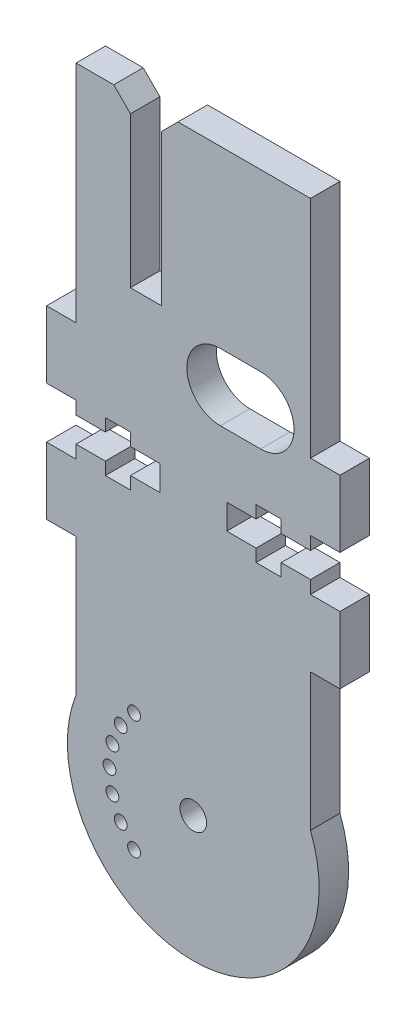
SolidWorks part; units mm, degrees
ref_plane "Front Plane" through (0, 0, 0) normal (0, 0, 1) x (1, 0, 0)
ref_plane "Top Plane" through (0, 0, 0) normal (0, 1, 0) x (1, 0, 0)
ref_plane "Right Plane" through (0, 0, 0) normal (1, 0, 0) x (0, 0, -1)
sketch "Sketch1" plane through (0, 0, 0) normal (0, 0, 1) x (1, 0, 0)
  line L0 (-6.0642, 85.6) -> (22.225, 85.6)
  line L1 (-22.225, 0) -> (22.225, 0)
  line L2 (-22.225, 0) -> (-22.225, 85.6)
  line L3 (-22.225, 85.6) -> (-11.9062, 85.6)
  line L4 (22.225, 0) -> (22.225, 85.6)
  line L6 (-11.9062, 85.6) -> (-11.9062, 53.85)
  line L7 (-11.9062, 53.85) -> (-6.0642, 53.85)
  line L8 (-6.0642, 85.6) -> (-6.0642, 53.85)
  dimension "D1" = 44.45
  dimension "D2" = 85.6
  dimension "D3" = 10.3187
  dimension "D4" = 31.75
  dimension "D5" = 5.842
extrude "Boss-Extrude1" add sketch "Sketch1" along normal mid plane 5.588
sketch "Sketch2" plane through (0, 0, 0) normal (0, 0, 1) x (1, 0, 0)
  line L0 (-22.225, 85.6) -> (-22.225, 0) construction
  line L3 (0, 0) -> (0, 25.4) construction
  line L5 (-6.35, 25.4) -> (6.35, 25.4) construction
  line B0 (-22.225, 27.7812) -> (-16.6688, 27.7812)
  line B1 (-22.225, 23.0187) -> (-16.6688, 23.0187)
  line B2 (-6.35, 27.7812) -> (-6.35, 23.0187)
  line B3 (-22.225, 27.7812) -> (-22.225, 23.0187)
  line B4 (-16.6688, 30.1625) -> (-11.9063, 30.1625)
  line B5 (-16.6688, 30.1625) -> (-16.6688, 27.7812)
  line B6 (-16.6688, 20.6375) -> (-11.9063, 20.6375)
  line B7 (-11.9063, 30.1625) -> (-11.9063, 27.7812)
  line B8 (-16.6688, 23.0187) -> (-16.6688, 20.6375)
  line B9 (-11.9063, 23.0187) -> (-11.9063, 20.6375)
  line B10 (-11.9063, 27.7812) -> (-6.35, 27.7812)
  line B11 (-11.9063, 23.0187) -> (-6.35, 23.0187)
  line B12 (22.225, 27.7812) -> (16.6688, 27.7812)
  line B13 (22.225, 23.0187) -> (16.6688, 23.0187)
  line B14 (6.35, 27.7812) -> (6.35, 23.0187)
  line B15 (22.225, 27.7812) -> (22.225, 23.0187)
  line B16 (16.6688, 30.1625) -> (11.9063, 30.1625)
  line B17 (16.6688, 30.1625) -> (16.6688, 27.7812)
  line B18 (16.6688, 20.6375) -> (11.9063, 20.6375)
  line B19 (11.9063, 30.1625) -> (11.9063, 27.7812)
  line B20 (16.6688, 23.0187) -> (16.6688, 20.6375)
  line B21 (11.9063, 23.0187) -> (11.9063, 20.6375)
  line B22 (11.9063, 27.7812) -> (6.35, 27.7812)
  line B23 (11.9063, 23.0187) -> (6.35, 23.0187)
  dimension "D1" = 25.4
sketch_block_instance "Block2-3"
sketch_block "Block2" parameters "D1"=4.7625, "D2"=4.7625, "D3"=5.5563, "D4"=5.5563
sketch_block_instance "Block2-5"
extrude "Cut-Extrude1" cut sketch "Sketch2" against normal through all both and the other way through all
sketch "Sketch3" plane through (0, 0, 0) normal (0, 0, 1) x (1, 0, 0)
  line L0 (-22.225, 23.0187) -> (-22.225, 0) construction
  line L1 (-22.225, 20.5583) -> (-27.813, 20.5583)
  line L2 (-22.225, 20.5583) -> (-22.225, 7.8583)
  line L3 (-22.225, 7.8583) -> (-27.813, 7.8583)
  line L4 (-27.813, 20.5583) -> (-27.813, 7.8583)
  line L5 (22.225, 0) -> (22.225, 23.0187) construction
  line L6 (22.225, 20.5583) -> (27.813, 20.5583)
  line L7 (22.225, 20.5583) -> (22.225, 7.8583)
  line L8 (22.225, 7.8583) -> (27.813, 7.8583)
  line L9 (27.813, 20.5583) -> (27.813, 7.8583)
  line L11 (-22.225, 85.6) -> (-22.225, 27.7812) construction
  line L12 (-22.225, 30.2417) -> (-27.813, 30.2417)
  line L13 (-22.225, 30.2417) -> (-22.225, 42.9417)
  line L14 (-22.225, 42.9417) -> (-27.813, 42.9417)
  line L15 (-27.813, 30.2417) -> (-27.813, 42.9417)
  line L16 (22.225, 27.7812) -> (22.225, 85.6) construction
  line L17 (22.225, 30.2417) -> (27.813, 30.2417)
  line L18 (22.225, 30.2417) -> (22.225, 42.9417)
  line L19 (22.225, 42.9417) -> (27.813, 42.9417)
  line L20 (27.813, 30.2417) -> (27.813, 42.9417)
  line L21 (-6.35, 25.4) -> (-25.019, 25.4) construction
  line L22 (-6.35, 23.0187) -> (-6.35, 27.7812) construction
  line L23 (-25.019, 30.2417) -> (-25.019, 20.5583) construction
  dimension "D1" = 12.7
  dimension "D2" = 9.6835
  dimension "D3" = 5.588
extrude "Boss-Extrude2" add sketch "Sketch3" along normal up to surface and the other way up to surface up to face at (-1.1232, 33.1156, 2.794) other way up to face at (-1.1232, 33.1156, -2.794)
sketch "Sketch4" plane through (0, 0, 0) normal (0, 0, 1) x (1, 0, 0)
  line L0 (0, -26.8554) -> (0, 0) construction
  line L3 (-22.225, 0) -> (22.225, 0)
  line L4 (-22.225, 0) -> (-22.225, -18.161)
  line L6 (22.225, 0) -> (22.225, -18.161)
  arc A0 (-22.225, -18.161) -> (22.225, -18.161) centre (0, -26.8554) ccw
  circle A1 centre (0, -26.8554) radius 2.5273
  dimension "D1" = 5.0546
  dimension "D2" = 47.7302
  dimension "D3" = 18.161
extrude "Boss-Extrude3" add sketch "Sketch4" along normal up to surface and the other way up to surface up to face at (-0.7488, 30.5438, 2.794) other way up to face at (-0.7488, 30.5438, -2.794)
sketch "Sketch5" plane through (0, 0, 2.794) normal (0, 0, 1) x (1, 0, 0)
  line L0 (-22.225, -26.8554) -> (-9.525, -26.8554) construction
  line L1 (-22.225, -26.5379) -> (-9.525, -26.5379)
  line L2 (-22.225, -27.1729) -> (-9.525, -27.1729)
  line L3 (-9.525, -26.8554) -> (0, -26.8554) construction
  line L4 (-21.9521, -11.8729) -> (-11.8422, -19.5593) construction
  line L5 (-21.7599, -11.6202) -> (-11.65, -19.3066)
  line L6 (-22.1442, -12.1257) -> (-12.0343, -19.812)
  line L7 (-12.667, -0.1113) -> (-9.271, -12.3488) construction
  line L8 (-12.361, -0.0264) -> (-8.9651, -12.2639)
  line L9 (-12.9729, -0.1962) -> (-9.577, -12.4337)
  line L10 (1.8429, 3.632) -> (-2.8602, -8.165) construction
  line L11 (2.1378, 3.5144) -> (-2.5653, -8.2826)
  line L12 (1.548, 3.7496) -> (-3.1552, -8.0475)
  line L13 (15.659, -2.1699) -> (4.7752, -8.7145) construction
  line L14 (15.8227, -2.442) -> (4.9388, -8.9866)
  line L15 (15.4954, -1.8978) -> (4.6116, -8.4424)
  line L16 (23.146, -15.1505) -> (10.5209, -13.7731) construction
  line L17 (23.1115, -15.4661) -> (10.4864, -14.0887)
  line L18 (23.1804, -14.8348) -> (10.5553, -13.4575)
  line L19 (21.2497, -30.0149) -> (12.0331, -21.2774) construction
  line L20 (21.0313, -30.2454) -> (11.8147, -21.5079)
  line L21 (21.4682, -29.7845) -> (12.2516, -21.047)
  line L22 (-8.9633, -41.3931) -> (-0.7298, -31.7236) construction
  line L23 (-9.205, -41.1873) -> (-0.9715, -31.5177)
  line L24 (-8.7215, -41.599) -> (-0.488, -31.9294)
  line L25 (-20.1937, -31.4721) -> (-7.7871, -28.7578) construction
  line L26 (-20.2615, -31.1619) -> (-7.855, -28.4476)
  line L27 (-20.1258, -31.7823) -> (-7.7192, -29.0679)
  line L28 (-23.1292, -16.7775) -> (-11.6101, -22.1255) construction
  line L29 (-22.9955, -16.4895) -> (-11.4764, -21.8376)
  line L30 (-23.2629, -17.0655) -> (-11.7438, -22.4135)
  line L31 (-16.5724, -3.3032) -> (-10.6394, -14.5321) construction
  line L32 (-16.2917, -3.1548) -> (-10.3587, -14.3838)
  line L33 (-16.8531, -3.4515) -> (-10.9201, -14.6805)
  line L34 (-3.1979, 3.4548) -> (-5.271, -9.0749) construction
  line L35 (-2.8846, 3.403) -> (-4.9577, -9.1267)
  line L36 (-3.5111, 3.5066) -> (-5.5842, -9.023)
  line L37 (11.5391, 0.7398) -> (2.3055, -7.9798) construction
  line L38 (11.7571, 0.509) -> (2.5235, -8.2106)
  line L39 (11.3211, 0.9706) -> (2.0875, -7.7489)
  line L2236 (-4.0864, -42.8478) -> (1.8684, -31.6304) construction
  line L2237 (-4.3668, -42.6989) -> (1.588, -31.4815)
  line L2238 (-3.806, -42.9967) -> (2.1488, -31.7793)
  line L2239 (-17.1918, -35.5817) -> (-5.6624, -30.2561) construction
  line L2240 (-17.325, -35.2935) -> (-5.7955, -29.9678)
  line L2241 (-17.0587, -35.8699) -> (-5.5293, -30.5443)
  line L2242 (-23.2268, -21.8658) -> (-10.8256, -24.6042) construction
  line L2243 (-23.1583, -21.5557) -> (-10.7571, -24.2942)
  line L2244 (-23.2953, -22.1758) -> (-10.894, -24.9142)
  line L2245 (-19.7297, -7.2946) -> (-11.515, -16.9801) construction
  line L2246 (-19.4876, -7.0892) -> (-11.2729, -16.7747)
  line L2247 (-19.9718, -7.5) -> (-11.7572, -17.1855)
  line L2248 (-8.1269, 2.1883) -> (-7.4496, -10.4937) construction
  line L2249 (-7.8099, 2.2052) -> (-7.1325, -10.4767)
  line L2250 (-8.444, 2.1713) -> (-7.7666, -10.5106)
  line L2251 (6.8487, 2.7148) -> (-0.2875, -7.7906) construction
  line L2252 (7.1114, 2.5364) -> (-0.0248, -7.969)
  line L2253 (6.5861, 2.8932) -> (-0.5501, -7.6122)
  line L2254 (19.0889, -5.9297) -> (7.0499, -9.9736) construction
  line L2255 (19.19, -6.2307) -> (7.151, -10.2745)
  line L2256 (18.9878, -5.6288) -> (6.9488, -9.6726)
  line L2257 (23.6007, -20.2193) -> (11.5696, -16.1521) construction
  line L2258 (23.499, -20.5201) -> (11.4679, -16.4528)
  line L2259 (23.7024, -19.9185) -> (11.6713, -15.8513)
  line L2260 (18.544, -34.3252) -> (11.4282, -23.8059) construction
  line L2261 (18.281, -34.5031) -> (11.1652, -23.9838)
  line L2262 (18.8069, -34.1473) -> (11.6911, -23.6281)
  line L2263 (5.9812, -42.4938) -> (6.6832, -29.8132) construction
  line L2264 (5.6642, -42.4763) -> (6.3662, -29.7957)
  line L2265 (6.2982, -42.5114) -> (7.0002, -29.8308)
  line L2266 (10.7439, -40.7002) -> (8.6951, -28.1666) construction
  line L2267 (10.4305, -40.7514) -> (8.3818, -28.2178)
  line L2268 (11.0572, -40.649) -> (9.0085, -28.1153)
  line L2269 (-4.0864, -42.8478) -> (1.8684, -31.6304) construction
  line L2270 (-4.3668, -42.6989) -> (1.588, -31.4815)
  line L2271 (-3.806, -42.9967) -> (2.1488, -31.7793)
  line L2272 (-17.1918, -35.5817) -> (-5.6624, -30.2561) construction
  line L2273 (-17.325, -35.2935) -> (-5.7955, -29.9678)
  line L2274 (-17.0587, -35.8699) -> (-5.5293, -30.5443)
  line L2275 (-23.2268, -21.8658) -> (-10.8256, -24.6042) construction
  line L2276 (-23.1583, -21.5557) -> (-10.7571, -24.2942)
  line L2277 (-23.2953, -22.1758) -> (-10.894, -24.9142)
  line L2278 (-19.7297, -7.2946) -> (-11.515, -16.9801) construction
  line L2279 (-19.4876, -7.0892) -> (-11.2729, -16.7747)
  line L2280 (-19.9718, -7.5) -> (-11.7572, -17.1855)
  line L2281 (-8.1269, 2.1883) -> (-7.4496, -10.4937) construction
  line L2282 (-7.8099, 2.2052) -> (-7.1325, -10.4767)
  line L2283 (-8.444, 2.1713) -> (-7.7666, -10.5106)
  line L2284 (6.8487, 2.7148) -> (-0.2875, -7.7906) construction
  line L2285 (7.1114, 2.5364) -> (-0.0248, -7.969)
  line L2286 (6.5861, 2.8932) -> (-0.5501, -7.6122)
  line L2287 (19.0889, -5.9297) -> (7.0499, -9.9736) construction
  line L2288 (19.19, -6.2307) -> (7.151, -10.2745)
  line L2289 (18.9878, -5.6288) -> (6.9488, -9.6726)
  line L2290 (23.6007, -20.2193) -> (11.5696, -16.1521) construction
  line L2291 (23.499, -20.5201) -> (11.4679, -16.4528)
  line L2292 (23.7024, -19.9185) -> (11.6713, -15.8513)
  line L2293 (18.544, -34.3252) -> (11.4282, -23.8059) construction
  line L2294 (18.281, -34.5031) -> (11.1652, -23.9838)
  line L2295 (18.8069, -34.1473) -> (11.6911, -23.6281)
  line L2296 (5.9812, -42.4938) -> (6.6832, -29.8132) construction
  line L2297 (5.6642, -42.4763) -> (6.3662, -29.7957)
  line L2298 (6.2982, -42.5114) -> (7.0002, -29.8308)
  line L2299 (10.7439, -40.7002) -> (8.6951, -28.1666) construction
  line L2300 (10.4305, -40.7514) -> (8.3818, -28.2178)
  line L2301 (11.0572, -40.649) -> (9.0085, -28.1153)
  arc A0 (-22.225, -26.5379) -> (-22.225, -27.1729) centre (-22.225, -26.8554) ccw
  arc A1 (-9.525, -27.1729) -> (-9.525, -26.5379) centre (-9.525, -26.8554) ccw
  arc A2 (-21.7599, -11.6202) -> (-22.1442, -12.1257) centre (-21.9521, -11.8729) ccw
  arc A3 (-12.0343, -19.812) -> (-11.65, -19.3066) centre (-11.8422, -19.5593) ccw
  arc A4 (-12.361, -0.0264) -> (-12.9729, -0.1962) centre (-12.667, -0.1113) ccw
  arc A5 (-9.577, -12.4337) -> (-8.9651, -12.2639) centre (-9.271, -12.3488) ccw
  arc A6 (2.1378, 3.5144) -> (1.548, 3.7496) centre (1.8429, 3.632) ccw
  arc A7 (-3.1552, -8.0475) -> (-2.5653, -8.2826) centre (-2.8602, -8.165) ccw
  arc A8 (15.8227, -2.442) -> (15.4954, -1.8978) centre (15.659, -2.1699) ccw
  arc A9 (4.6116, -8.4424) -> (4.9388, -8.9866) centre (4.7752, -8.7145) ccw
  arc A10 (23.1115, -15.4661) -> (23.1804, -14.8348) centre (23.146, -15.1505) ccw
  arc A11 (10.5553, -13.4575) -> (10.4864, -14.0887) centre (10.5209, -13.7731) ccw
  arc A12 (21.0313, -30.2454) -> (21.4682, -29.7845) centre (21.2497, -30.0149) ccw
  arc A13 (12.2516, -21.047) -> (11.8147, -21.5079) centre (12.0331, -21.2774) ccw
  arc A14 (-9.205, -41.1873) -> (-8.7215, -41.599) centre (-8.9633, -41.3931) ccw
  arc A15 (-0.488, -31.9294) -> (-0.9715, -31.5177) centre (-0.7298, -31.7236) ccw
  arc A16 (-20.2615, -31.1619) -> (-20.1258, -31.7823) centre (-20.1937, -31.4721) ccw
  arc A17 (-7.7192, -29.0679) -> (-7.855, -28.4476) centre (-7.7871, -28.7578) ccw
  arc A18 (-22.9955, -16.4895) -> (-23.2629, -17.0655) centre (-23.1292, -16.7775) ccw
  arc A19 (-11.7438, -22.4135) -> (-11.4764, -21.8376) centre (-11.6101, -22.1255) ccw
  arc A20 (-16.2917, -3.1548) -> (-16.8531, -3.4515) centre (-16.5724, -3.3032) ccw
  arc A21 (-10.9201, -14.6805) -> (-10.3587, -14.3838) centre (-10.6394, -14.5321) ccw
  arc A22 (-2.8846, 3.403) -> (-3.5111, 3.5066) centre (-3.1979, 3.4548) ccw
  arc A23 (-5.5842, -9.023) -> (-4.9577, -9.1267) centre (-5.271, -9.0749) ccw
  arc A24 (11.7571, 0.509) -> (11.3211, 0.9706) centre (11.5391, 0.7398) ccw
  arc A25 (2.0875, -7.7489) -> (2.5235, -8.2106) centre (2.3055, -7.9798) ccw
  arc A1512 (-4.3668, -42.6989) -> (-3.806, -42.9967) centre (-4.0864, -42.8478) ccw
  arc A1513 (2.1488, -31.7793) -> (1.588, -31.4815) centre (1.8684, -31.6304) ccw
  arc A1514 (-17.325, -35.2935) -> (-17.0587, -35.8699) centre (-17.1918, -35.5817) ccw
  arc A1515 (-5.5293, -30.5443) -> (-5.7955, -29.9678) centre (-5.6624, -30.2561) ccw
  arc A1516 (-23.1583, -21.5557) -> (-23.2953, -22.1758) centre (-23.2268, -21.8658) ccw
  arc A1517 (-10.894, -24.9142) -> (-10.7571, -24.2942) centre (-10.8256, -24.6042) ccw
  arc A1518 (-19.4876, -7.0892) -> (-19.9718, -7.5) centre (-19.7297, -7.2946) ccw
  arc A1519 (-11.7572, -17.1855) -> (-11.2729, -16.7747) centre (-11.515, -16.9801) ccw
  arc A1520 (-7.8099, 2.2052) -> (-8.444, 2.1713) centre (-8.1269, 2.1883) ccw
  arc A1521 (-7.7666, -10.5106) -> (-7.1325, -10.4767) centre (-7.4496, -10.4937) ccw
  arc A1522 (7.1114, 2.5364) -> (6.5861, 2.8932) centre (6.8487, 2.7148) ccw
  arc A1523 (-0.5501, -7.6122) -> (-0.0248, -7.969) centre (-0.2875, -7.7906) ccw
  arc A1524 (19.19, -6.2307) -> (18.9878, -5.6288) centre (19.0889, -5.9297) ccw
  arc A1525 (6.9488, -9.6726) -> (7.151, -10.2745) centre (7.0499, -9.9736) ccw
  arc A1526 (23.499, -20.5201) -> (23.7024, -19.9185) centre (23.6007, -20.2193) ccw
  arc A1527 (11.6713, -15.8513) -> (11.4679, -16.4528) centre (11.5696, -16.1521) ccw
  arc A1528 (18.281, -34.5031) -> (18.8069, -34.1473) centre (18.544, -34.3252) ccw
  arc A1529 (11.6911, -23.6281) -> (11.1652, -23.9838) centre (11.4282, -23.8059) ccw
  arc A1530 (5.6642, -42.4763) -> (6.2982, -42.5114) centre (5.9812, -42.4938) ccw
  arc A1531 (7.0002, -29.8308) -> (6.3662, -29.7957) centre (6.6832, -29.8132) ccw
  arc A1532 (10.4305, -40.7514) -> (11.0572, -40.649) centre (10.7439, -40.7002) ccw
  arc A1533 (9.0085, -28.1153) -> (8.3818, -28.2178) centre (8.6951, -28.1666) ccw
  point P2 (-15.875, -26.8554)
  point P15 (-16.8971, -15.7161)
  point P22 (-10.969, -6.2301)
  point P29 (-0.5087, -2.2665)
  point P36 (10.2171, -5.4422)
  point P43 (16.8334, -14.4618)
  point P50 (16.6414, -25.6462)
  point P55 (0.1422, -19.7691)
  point P57 (-4.8465, -36.5583)
  point P58 (7.9375, -0.6268)
  point P65 (11.2253, -3.1497)
  point P66 (-13.9904, -30.1149)
  point P72 (13.7482, -6.4375)
  point P74 (-17.3696, -19.4515)
  point P79 (15.3341, -10.2662)
  point P82 (-13.6059, -8.9176)
  point P86 (15.875, -14.375)
  point P90 (-4.2344, -2.81)
  point P93 (15.3341, -18.4837)
  point P98 (6.9223, -3.62)
  point P100 (13.7482, -22.3125)
  point P107 (11.2253, -25.6003)
  point P114 (7.9375, -28.1231)
  point P121 (4.1088, -29.7091)
  point P135 (4.1088, 0.9591)
  point P142 (7.9375, -0.6268)
  point P149 (11.2253, -3.1497)
  point P156 (13.7482, -6.4375)
  point P163 (15.3341, -10.2662)
  point P170 (15.875, -14.375)
  point P177 (15.3341, -18.4837)
  point P184 (13.7482, -22.3125)
  point P191 (11.2253, -25.6003)
  point P198 (7.9375, -28.1231)
  point P205 (4.1088, -29.7091)
  point P212 (4.1088, 0.9591)
  point P219 (7.9375, -0.6268)
  point P226 (11.2253, -3.1497)
  point P233 (13.7482, -6.4375)
  point P240 (15.3341, -10.2662)
  point P247 (15.875, -14.375)
  point P254 (15.3341, -18.4837)
  point P261 (13.7482, -22.3125)
  point P268 (11.2253, -25.6003)
  point P275 (7.9375, -28.1231)
  point P282 (4.1088, -29.7091)
  point P289 (4.1088, 0.9591)
  point P296 (7.9375, -0.6268)
  point P303 (11.2253, -3.1497)
  point P310 (13.7482, -6.4375)
  point P317 (15.3341, -10.2662)
  point P324 (15.875, -14.375)
  point P331 (15.3341, -18.4837)
  point P338 (13.7482, -22.3125)
  point P345 (11.2253, -25.6003)
  point P352 (7.9375, -28.1231)
  point P359 (4.1088, -29.7091)
  point P366 (4.1088, 0.9591)
  point P373 (7.9375, -0.6268)
  point P380 (11.2253, -3.1497)
  point P387 (13.7482, -6.4375)
  point P394 (15.3341, -10.2662)
  point P401 (15.875, -14.375)
  point P408 (15.3341, -18.4837)
  point P415 (13.7482, -22.3125)
  point P422 (11.2253, -25.6003)
  point P429 (7.9375, -28.1231)
  point P436 (4.1088, -29.7091)
  point P443 (4.1088, 0.9591)
  point P450 (7.9375, -0.6268)
  point P457 (11.2253, -3.1497)
  point P464 (13.7482, -6.4375)
  point P471 (15.3341, -10.2662)
  point P478 (15.875, -14.375)
  point P485 (15.3341, -18.4837)
  point P492 (13.7482, -22.3125)
  point P499 (11.2253, -25.6003)
  point P506 (7.9375, -28.1231)
  point P513 (4.1088, -29.7091)
  point P520 (4.1088, 0.9591)
  point P527 (7.9375, -0.6268)
  point P534 (11.2253, -3.1497)
  point P541 (13.7482, -6.4375)
  point P548 (15.3341, -10.2662)
  point P555 (15.875, -14.375)
  point P562 (15.3341, -18.4837)
  point P569 (13.7482, -22.3125)
  point P576 (11.2253, -25.6003)
  point P583 (7.9375, -28.1231)
  point P590 (4.1088, -29.7091)
  point P597 (4.1088, 0.9591)
  point P604 (7.9375, -0.6268)
  point P611 (11.2253, -3.1497)
  point P618 (13.7482, -6.4375)
  point P625 (15.3341, -10.2662)
  point P632 (15.875, -14.375)
  point P639 (15.3341, -18.4837)
  point P646 (13.7482, -22.3125)
  point P653 (11.2253, -25.6003)
  point P660 (7.9375, -28.1231)
  point P667 (4.1088, -29.7091)
  point P674 (4.1088, 0.9591)
  point P681 (7.9375, -0.6268)
  point P688 (11.2253, -3.1497)
  point P695 (13.7482, -6.4375)
  point P702 (15.3341, -10.2662)
  point P709 (15.875, -14.375)
  point P716 (15.3341, -18.4837)
  point P723 (13.7482, -22.3125)
  point P730 (11.2253, -25.6003)
  point P737 (7.9375, -28.1231)
  point P744 (4.1088, -29.7091)
  point P751 (4.1088, 0.9591)
  point P758 (7.9375, -0.6268)
  point P765 (11.2253, -3.1497)
  point P772 (13.7482, -6.4375)
  point P779 (15.3341, -10.2662)
  point P786 (15.875, -14.375)
  point P793 (15.3341, -18.4837)
  point P800 (13.7482, -22.3125)
  point P807 (11.2253, -25.6003)
  point P814 (7.9375, -28.1231)
  point P821 (4.1088, -29.7091)
  point P828 (4.1088, 0.9591)
  point P835 (7.9375, -0.6268)
  point P842 (11.2253, -3.1497)
  point P849 (13.7482, -6.4375)
  point P856 (15.3341, -10.2662)
  point P863 (15.875, -14.375)
  point P870 (15.3341, -18.4837)
  point P877 (13.7482, -22.3125)
  point P884 (11.2253, -25.6003)
  point P891 (7.9375, -28.1231)
  point P898 (4.1088, -29.7091)
  point P905 (4.1088, 0.9591)
  point P912 (7.9375, -0.6268)
  point P919 (11.2253, -3.1497)
  point P926 (13.7482, -6.4375)
  point P933 (15.3341, -10.2662)
  point P940 (15.875, -14.375)
  point P947 (15.3341, -18.4837)
  point P954 (13.7482, -22.3125)
  point P961 (11.2253, -25.6003)
  point P968 (7.9375, -28.1231)
  point P975 (4.1088, -29.7091)
  point P982 (4.1088, 0.9591)
  point P989 (7.9375, -0.6268)
  point P996 (11.2253, -3.1497)
  point P1003 (13.7482, -6.4375)
  point P1010 (15.3341, -10.2662)
  point P1017 (15.875, -14.375)
  point P1024 (15.3341, -18.4837)
  point P1031 (13.7482, -22.3125)
  point P1038 (11.2253, -25.6003)
  point P1045 (7.9375, -28.1231)
  point P1052 (4.1088, -29.7091)
  point P1059 (4.1088, 0.9591)
  point P1066 (7.9375, -0.6268)
  point P1073 (11.2253, -3.1497)
  point P1080 (13.7482, -6.4375)
  point P1087 (15.3341, -10.2662)
  point P1094 (15.875, -14.375)
  point P1101 (15.3341, -18.4837)
  point P1108 (13.7482, -22.3125)
  point P1115 (11.2253, -25.6003)
  point P1122 (7.9375, -28.1231)
  point P1129 (4.1088, -29.7091)
  point P1136 (4.1088, 0.9591)
  point P1143 (10.4461, -0.4689)
  point P1150 (13.2192, -3.4761)
  point P1157 (15.1591, -7.0775)
  point P1164 (16.1444, -11.0477)
  point P1171 (16.1133, -15.1382)
  point P1178 (15.0679, -19.093)
  point P1185 (13.0736, -22.6646)
  point P1192 (10.2552, -25.6294)
  point P1199 (6.7891, -27.8018)
  point P1206 (2.8922, -29.0459)
  point P1213 (7.0134, 1.7559)
  point P1220 (10.4461, -0.4689)
  point P1227 (13.2192, -3.4761)
  point P1234 (15.1591, -7.0775)
  point P1241 (16.1444, -11.0477)
  point P1248 (16.1133, -15.1382)
  point P1255 (15.0679, -19.093)
  point P1262 (13.0736, -22.6646)
  point P1269 (10.2552, -25.6294)
  point P1276 (6.7891, -27.8018)
  point P1283 (2.8922, -29.0459)
  point P1290 (7.0134, 1.7559)
  point P1297 (10.4461, -0.4689)
  point P1304 (13.2192, -3.4761)
  point P1311 (15.1591, -7.0775)
  point P1318 (16.1444, -11.0477)
  point P1325 (16.1133, -15.1382)
  point P1332 (15.0679, -19.093)
  point P1339 (13.0736, -22.6646)
  point P1346 (10.2552, -25.6294)
  point P1353 (6.7891, -27.8018)
  point P1360 (2.8922, -29.0459)
  point P1367 (7.0134, 1.7559)
  point P1374 (10.4461, -0.4689)
  point P1381 (13.2192, -3.4761)
  point P1388 (15.1591, -7.0775)
  point P1395 (16.1444, -11.0477)
  point P1402 (16.1133, -15.1382)
  point P1409 (15.0679, -19.093)
  point P1416 (13.0736, -22.6646)
  point P1423 (10.2552, -25.6294)
  point P1430 (6.7891, -27.8018)
  point P1437 (2.8922, -29.0459)
  point P1444 (7.0134, 1.7559)
  point P1451 (10.4461, -0.4689)
  point P1458 (13.2192, -3.4761)
  point P1465 (15.1591, -7.0775)
  point P1472 (16.1444, -11.0477)
  point P1479 (16.1133, -15.1382)
  point P1486 (15.0679, -19.093)
  point P1493 (13.0736, -22.6646)
  point P1500 (10.2552, -25.6294)
  point P1507 (6.7891, -27.8018)
  point P1514 (2.8922, -29.0459)
  point P1521 (7.0134, 1.7559)
  point P1528 (10.4461, -0.4689)
  point P1535 (13.2192, -3.4761)
  point P1542 (15.1591, -7.0775)
  point P1549 (16.1444, -11.0477)
  point P1556 (16.1133, -15.1382)
  point P1563 (15.0679, -19.093)
  point P1570 (13.0736, -22.6646)
  point P1577 (10.2552, -25.6294)
  point P1584 (6.7891, -27.8018)
  point P1591 (2.8922, -29.0459)
  point P1598 (7.0134, 1.7559)
  point P1605 (9.279, -0.938)
  point P1612 (12.2925, -3.7244)
  point P1619 (14.4989, -7.1851)
  point P1626 (15.7534, -11.0929)
  point P1633 (15.9737, -15.1912)
  point P1640 (15.1453, -19.211)
  point P1647 (13.3226, -22.8883)
  point P1654 (10.6253, -25.9817)
  point P1661 (7.2304, -28.288)
  point P1668 (3.3608, -29.656)
  point P1675 (5.6565, 0.9911)
  point P1682 (9.279, -0.938)
  point P1689 (12.2925, -3.7244)
  point P1696 (14.4989, -7.1851)
  point P1703 (15.7534, -11.0929)
  point P1710 (15.9737, -15.1912)
  point P1717 (15.1453, -19.211)
  point P1724 (13.3226, -22.8883)
  point P1731 (10.6253, -25.9817)
  point P1738 (7.2304, -28.288)
  point P1745 (3.3608, -29.656)
  point P1752 (5.6565, 0.9911)
  point P1759 (7.5387, -0.2508)
  point P1766 (10.9414, -2.6831)
  point P1773 (13.5942, -5.9167)
  point P1780 (15.3147, -9.7291)
  point P1787 (15.9843, -13.8577)
  point P1794 (15.557, -18.0184)
  point P1801 (14.0621, -21.9248)
  point P1808 (11.6026, -25.3078)
  point P1815 (8.3479, -27.9347)
  point P1822 (4.5219, -29.6246)
  point P1829 (3.6205, 1.2127)
  point P1836 (7.5387, -0.2508)
  point P1843 (10.9414, -2.6831)
  point P1850 (13.5942, -5.9167)
  point P1857 (15.3147, -9.7291)
  point P1864 (15.9843, -13.8577)
  point P1871 (15.557, -18.0184)
  point P1878 (14.0621, -21.9248)
  point P1885 (11.6026, -25.3078)
  point P1892 (8.3479, -27.9347)
  point P1899 (4.5219, -29.6246)
  point P1906 (3.6205, 1.2127)
  point P1913 (7.5387, -0.2508)
  point P1920 (10.9414, -2.6831)
  point P1927 (13.5942, -5.9167)
  point P1934 (15.3147, -9.7291)
  point P1941 (15.9843, -13.8577)
  point P1948 (15.557, -18.0184)
  point P1955 (14.0621, -21.9248)
  point P1962 (11.6026, -25.3078)
  point P1969 (8.3479, -27.9347)
  point P1976 (4.5219, -29.6246)
  point P1983 (3.6205, 1.2127)
  point P1990 (7.5387, -0.2508)
  point P1997 (10.9414, -2.6831)
  point P2004 (13.5942, -5.9167)
  point P2011 (15.3147, -9.7291)
  point P2018 (15.9843, -13.8577)
  point P2025 (15.557, -18.0184)
  point P2032 (14.0621, -21.9248)
  point P2039 (11.6026, -25.3078)
  point P2046 (8.3479, -27.9347)
  point P2053 (4.5219, -29.6246)
  point P2060 (3.6205, 1.2127)
  point P2067 (7.5387, -0.2508)
  point P2074 (10.9414, -2.6831)
  point P2081 (13.5942, -5.9167)
  point P2088 (15.3147, -9.7291)
  point P2095 (15.9843, -13.8577)
  point P2102 (15.557, -18.0184)
  point P2109 (14.0621, -21.9248)
  point P2116 (11.6026, -25.3078)
  point P2123 (8.3479, -27.9347)
  point P2130 (4.5219, -29.6246)
  point P2137 (3.6205, 1.2127)
  point P2144 (7.5387, -0.2508)
  point P2151 (10.9414, -2.6831)
  point P2158 (13.5942, -5.9167)
  point P2165 (15.3147, -9.7291)
  point P2172 (15.9843, -13.8577)
  point P2179 (15.557, -18.0184)
  point P2186 (14.0621, -21.9248)
  point P2193 (11.6026, -25.3078)
  point P2200 (8.3479, -27.9347)
  point P2207 (4.5219, -29.6246)
  point P2214 (3.6205, 1.2127)
  point P2221 (7.5387, -0.2508)
  point P2228 (10.9414, -2.6831)
  point P2235 (13.5942, -5.9167)
  point P2242 (15.3147, -9.7291)
  point P2249 (15.9843, -13.8577)
  point P2256 (15.557, -18.0184)
  point P2263 (14.0621, -21.9248)
  point P2270 (11.6026, -25.3078)
  point P2277 (8.3479, -27.9347)
  point P2284 (4.5219, -29.6246)
  point P2291 (3.6205, 1.2127)
  point P2298 (7.5387, -0.2508)
  point P2305 (10.9414, -2.6831)
  point P2312 (13.5942, -5.9167)
  point P2319 (15.3147, -9.7291)
  point P2326 (15.9843, -13.8577)
  point P2333 (15.557, -18.0184)
  point P2340 (14.0621, -21.9248)
  point P2347 (11.6026, -25.3078)
  point P2354 (8.3479, -27.9347)
  point P2361 (4.5219, -29.6246)
  point P2368 (3.6205, 1.2127)
  point P2375 (7.5387, -0.2508)
  point P2382 (10.9414, -2.6831)
  point P2389 (13.5942, -5.9167)
  point P2396 (15.3147, -9.7291)
  point P2403 (15.9843, -13.8577)
  point P2410 (15.557, -18.0184)
  point P2417 (14.0621, -21.9248)
  point P2424 (11.6026, -25.3078)
  point P2431 (8.3479, -27.9347)
  point P2438 (4.5219, -29.6246)
  point P2445 (3.6205, 1.2127)
  point P2452 (7.5387, -0.2508)
  point P2459 (10.9414, -2.6831)
  point P2466 (13.5942, -5.9167)
  point P2473 (15.3147, -9.7291)
  point P2480 (15.9843, -13.8577)
  point P2487 (15.557, -18.0184)
  point P2494 (14.0621, -21.9248)
  point P2501 (11.6026, -25.3078)
  point P2508 (8.3479, -27.9347)
  point P2515 (4.5219, -29.6246)
  point P2522 (3.6205, 1.2127)
  point P2529 (7.5387, -0.2508)
  point P2536 (10.9414, -2.6831)
  point P2543 (13.5942, -5.9167)
  point P2550 (15.3147, -9.7291)
  point P2557 (15.9843, -13.8577)
  point P2564 (15.557, -18.0184)
  point P2571 (14.0621, -21.9248)
  point P2578 (11.6026, -25.3078)
  point P2585 (8.3479, -27.9347)
  point P2592 (4.5219, -29.6246)
  point P2599 (3.6205, 1.2127)
  point P2606 (7.5387, -0.2508)
  point P2613 (10.9414, -2.6831)
  point P2620 (13.5942, -5.9167)
  point P2627 (15.3147, -9.7291)
  point P2634 (15.9843, -13.8577)
  point P2641 (15.557, -18.0184)
  point P2648 (14.0621, -21.9248)
  point P2655 (11.6026, -25.3078)
  point P2662 (8.3479, -27.9347)
  point P2669 (4.5219, -29.6246)
  point P2676 (3.6205, 1.2127)
  point P2683 (7.5387, -0.2508)
  point P2690 (10.9414, -2.6831)
  point P2697 (13.5942, -5.9167)
  point P2704 (15.3147, -9.7291)
  point P2711 (15.9843, -13.8577)
  point P2718 (15.557, -18.0184)
  point P2725 (14.0621, -21.9248)
  point P2732 (11.6026, -25.3078)
  point P2739 (8.3479, -27.9347)
  point P2746 (4.5219, -29.6246)
  point P2753 (3.6205, 1.2127)
  point P2760 (7.5387, -0.2508)
  point P2767 (10.9414, -2.6831)
  point P2774 (13.5942, -5.9167)
  point P2781 (15.3147, -9.7291)
  point P2788 (15.9843, -13.8577)
  point P2795 (15.557, -18.0184)
  point P2802 (14.0621, -21.9248)
  point P2809 (11.6026, -25.3078)
  point P2816 (8.3479, -27.9347)
  point P2823 (4.5219, -29.6246)
  point P2830 (3.6205, 1.2127)
  point P2837 (7.5387, -0.2508)
  point P2844 (10.9414, -2.6831)
  point P2851 (13.5942, -5.9167)
  point P2858 (15.3147, -9.7291)
  point P2865 (15.9843, -13.8577)
  point P2872 (15.557, -18.0184)
  point P2879 (14.0621, -21.9248)
  point P2886 (11.6026, -25.3078)
  point P2893 (8.3479, -27.9347)
  point P2900 (4.5219, -29.6246)
  point P2907 (3.6205, 1.2127)
  point P2914 (7.5387, -0.2508)
  point P2921 (10.9414, -2.6831)
  point P2928 (13.5942, -5.9167)
  point P2935 (15.3147, -9.7291)
  point P2942 (15.9843, -13.8577)
  point P2949 (15.557, -18.0184)
  point P2956 (14.0621, -21.9248)
  point P2963 (11.6026, -25.3078)
  point P2970 (8.3479, -27.9347)
  point P2977 (4.5219, -29.6246)
  point P2984 (3.6205, 1.2127)
  point P2991 (7.5387, -0.2508)
  point P2998 (10.9414, -2.6831)
  point P3005 (13.5942, -5.9167)
  point P3012 (15.3147, -9.7291)
  point P3019 (15.9843, -13.8577)
  point P3026 (15.557, -18.0184)
  point P3033 (14.0621, -21.9248)
  point P3040 (11.6026, -25.3078)
  point P3047 (8.3479, -27.9347)
  point P3054 (4.5219, -29.6246)
  point P3061 (3.6205, 1.2127)
  point P3068 (7.5387, -0.2508)
  point P3075 (10.9414, -2.6831)
  point P3082 (13.5942, -5.9167)
  point P3089 (15.3147, -9.7291)
  point P3096 (15.9843, -13.8577)
  point P3103 (15.557, -18.0184)
  point P3110 (14.0621, -21.9248)
  point P3117 (11.6026, -25.3078)
  point P3124 (8.3479, -27.9347)
  point P3131 (4.5219, -29.6246)
  point P3138 (3.6205, 1.2127)
  point P3145 (7.5387, -0.2508)
  point P3152 (10.9414, -2.6831)
  point P3159 (13.5942, -5.9167)
  point P3166 (15.3147, -9.7291)
  point P3173 (15.9843, -13.8577)
  point P3180 (15.557, -18.0184)
  point P3187 (14.0621, -21.9248)
  point P3194 (11.6026, -25.3078)
  point P3201 (8.3479, -27.9347)
  point P3208 (4.5219, -29.6246)
  point P3215 (3.6205, 1.2127)
  point P3222 (7.5387, -0.2508)
  point P3229 (10.9414, -2.6831)
  point P3236 (13.5942, -5.9167)
  point P3243 (15.3147, -9.7291)
  point P3250 (15.9843, -13.8577)
  point P3257 (15.557, -18.0184)
  point P3264 (14.0621, -21.9248)
  point P3271 (11.6026, -25.3078)
  point P3278 (8.3479, -27.9347)
  point P3285 (4.5219, -29.6246)
  point P3292 (3.6205, 1.2127)
  point P3299 (7.5387, -0.2508)
  point P3306 (10.9414, -2.6831)
  point P3313 (13.5942, -5.9167)
  point P3320 (15.3147, -9.7291)
  point P3327 (15.9843, -13.8577)
  point P3334 (15.557, -18.0184)
  point P3341 (14.0621, -21.9248)
  point P3348 (11.6026, -25.3078)
  point P3355 (8.3479, -27.9347)
  point P3362 (4.5219, -29.6246)
  point P3369 (3.6205, 1.2127)
  point P3376 (7.5387, -0.2508)
  point P3383 (10.9414, -2.6831)
  point P3390 (13.5942, -5.9167)
  point P3397 (15.3147, -9.7291)
  point P3404 (15.9843, -13.8577)
  point P3411 (15.557, -18.0184)
  point P3418 (14.0621, -21.9248)
  point P3425 (11.6026, -25.3078)
  point P3432 (8.3479, -27.9347)
  point P3439 (4.5219, -29.6246)
  point P3446 (3.6205, 1.2127)
  point P3453 (7.5387, -0.2508)
  point P3460 (10.9414, -2.6831)
  point P3467 (13.5942, -5.9167)
  point P3474 (15.3147, -9.7291)
  point P3481 (15.9843, -13.8577)
  point P3488 (15.557, -18.0184)
  point P3495 (14.0621, -21.9248)
  point P3502 (11.6026, -25.3078)
  point P3509 (8.3479, -27.9347)
  point P3516 (4.5219, -29.6246)
  point P3523 (3.6205, 1.2127)
  point P3530 (7.5387, -0.2508)
  point P3537 (10.9414, -2.6831)
  point P3544 (13.5942, -5.9167)
  point P3551 (15.3147, -9.7291)
  point P3558 (15.9843, -13.8577)
  point P3565 (15.557, -18.0184)
  point P3572 (14.0621, -21.9248)
  point P3579 (11.6026, -25.3078)
  point P3586 (8.3479, -27.9347)
  point P3593 (4.5219, -29.6246)
  point P3600 (3.6205, 1.2127)
  point P3607 (7.5387, -0.2508)
  point P3614 (10.9414, -2.6831)
  point P3621 (13.5942, -5.9167)
  point P3628 (15.3147, -9.7291)
  point P3635 (15.9843, -13.8577)
  point P3642 (15.557, -18.0184)
  point P3649 (14.0621, -21.9248)
  point P3656 (11.6026, -25.3078)
  point P3663 (8.3479, -27.9347)
  point P3670 (4.5219, -29.6246)
  point P3677 (3.6205, 1.2127)
  point P3684 (7.5387, -0.2508)
  point P3691 (10.9414, -2.6831)
  point P3698 (13.5942, -5.9167)
  point P3705 (15.3147, -9.7291)
  point P3712 (15.9843, -13.8577)
  point P3719 (15.557, -18.0184)
  point P3726 (14.0621, -21.9248)
  point P3733 (11.6026, -25.3078)
  point P3740 (8.3479, -27.9347)
  point P3747 (4.5219, -29.6246)
  point P3754 (3.6205, 1.2127)
  point P3761 (7.5387, -0.2508)
  point P3768 (10.9414, -2.6831)
  point P3775 (13.5942, -5.9167)
  point P3782 (15.3147, -9.7291)
  point P3789 (15.9843, -13.8577)
  point P3796 (15.557, -18.0184)
  point P3803 (14.0621, -21.9248)
  point P3810 (11.6026, -25.3078)
  point P3817 (8.3479, -27.9347)
  point P3824 (4.5219, -29.6246)
  point P3831 (3.6205, 1.2127)
  point P3838 (7.5387, -0.2508)
  point P3845 (10.9414, -2.6831)
  point P3852 (13.5942, -5.9167)
  point P3859 (15.3147, -9.7291)
  point P3866 (15.9843, -13.8577)
  point P3873 (15.557, -18.0184)
  point P3880 (14.0621, -21.9248)
  point P3887 (11.6026, -25.3078)
  point P3894 (8.3479, -27.9347)
  point P3901 (4.5219, -29.6246)
  point P3908 (3.6205, 1.2127)
  point P3915 (7.5387, -0.2508)
  point P3922 (10.9414, -2.6831)
  point P3929 (13.5942, -5.9167)
  point P3936 (15.3147, -9.7291)
  point P3943 (15.9843, -13.8577)
  point P3950 (15.557, -18.0184)
  point P3957 (14.0621, -21.9248)
  point P3964 (11.6026, -25.3078)
  point P3971 (8.3479, -27.9347)
  point P3978 (4.5219, -29.6246)
  point P3985 (3.6205, 1.2127)
  point P3992 (7.5387, -0.2508)
  point P3999 (10.9414, -2.6831)
  point P4006 (13.5942, -5.9167)
  point P4013 (15.3147, -9.7291)
  point P4020 (15.9843, -13.8577)
  point P4027 (15.557, -18.0184)
  point P4034 (14.0621, -21.9248)
  point P4041 (11.6026, -25.3078)
  point P4048 (8.3479, -27.9347)
  point P4055 (4.5219, -29.6246)
  point P4062 (3.6205, 1.2127)
  point P4069 (7.5387, -0.2508)
  point P4076 (10.9414, -2.6831)
  point P4083 (13.5942, -5.9167)
  point P4090 (15.3147, -9.7291)
  point P4097 (15.9843, -13.8577)
  point P4104 (15.557, -18.0184)
  point P4111 (14.0621, -21.9248)
  point P4118 (11.6026, -25.3078)
  point P4125 (8.3479, -27.9347)
  point P4132 (4.5219, -29.6246)
  point P4139 (3.6205, 1.2127)
  point P4146 (7.5387, -0.2508)
  point P4153 (10.9414, -2.6831)
  point P4160 (13.5942, -5.9167)
  point P4167 (15.3147, -9.7291)
  point P4174 (15.9843, -13.8577)
  point P4181 (15.557, -18.0184)
  point P4188 (14.0621, -21.9248)
  point P4195 (11.6026, -25.3078)
  point P4202 (8.3479, -27.9347)
  point P4209 (4.5219, -29.6246)
  point P4216 (3.6205, 1.2127)
  point P4223 (7.5387, -0.2508)
  point P4230 (10.9414, -2.6831)
  point P4237 (13.5942, -5.9167)
  point P4244 (15.3147, -9.7291)
  point P4251 (15.9843, -13.8577)
  point P4258 (15.557, -18.0184)
  point P4265 (14.0621, -21.9248)
  point P4272 (11.6026, -25.3078)
  point P4279 (8.3479, -27.9347)
  point P4286 (4.5219, -29.6246)
  point P4293 (3.6205, 1.2127)
  point P4300 (7.5387, -0.2508)
  point P4307 (10.9414, -2.6831)
  point P4314 (13.5942, -5.9167)
  point P4321 (15.3147, -9.7291)
  point P4328 (15.9843, -13.8577)
  point P4335 (15.557, -18.0184)
  point P4342 (14.0621, -21.9248)
  point P4349 (11.6026, -25.3078)
  point P4356 (8.3479, -27.9347)
  point P4363 (4.5219, -29.6246)
  point P4370 (3.6205, 1.2127)
  point P4377 (-0.9508, -34.4208)
  point P4384 (-10.9996, -30.4835)
  point P4391 (-16.6741, -21.303)
  point P4398 (-15.7028, -10.5542)
  point P4405 (-8.4745, -2.5396)
  point P4412 (2.1174, -0.4676)
  point P4419 (11.833, -5.1674)
  point P4426 (16.7832, -14.7578)
  point P4433 (14.9866, -25.3999)
  point P4440 (7.1622, -32.8336)
  point P4447 (9.4499, -31.5387)
  point P4454 (-0.9508, -34.4208)
  point P4461 (-10.9996, -30.4835)
  point P4468 (-16.6741, -21.303)
  point P4475 (-15.7028, -10.5542)
  point P4482 (-8.4745, -2.5396)
  point P4489 (2.1174, -0.4676)
  point P4496 (11.833, -5.1674)
  point P4503 (16.7832, -14.7578)
  point P4510 (14.9866, -25.3999)
  point P4517 (7.1622, -32.8336)
  point P4524 (9.4499, -31.5387)
  point P4531 (-1.109, -37.2391)
  point P4538 (-11.4271, -32.9189)
  point P4545 (-17.0262, -23.235)
  point P4552 (-15.6224, -12.1373)
  point P4559 (-7.7883, -4.1527)
  point P4566 (3.2806, -2.5379)
  point P4573 (13.0694, -7.9516)
  point P4580 (17.5852, -18.1857)
  point P4587 (14.9861, -29.0656)
  point P4594 (6.3322, -36.1535)
  point P4601 (9.7195, -34.4334)
  point P4608 (-1.109, -37.2391)
  point P4615 (-11.4271, -32.9189)
  point P4622 (-17.0262, -23.235)
  point P4629 (-15.6224, -12.1373)
  point P4636 (-7.7883, -4.1527)
  point P4643 (3.2806, -2.5379)
  point P4650 (13.0694, -7.9516)
  point P4657 (17.5852, -18.1857)
  point P4664 (14.9861, -29.0656)
  point P4671 (6.3322, -36.1535)
  point P4678 (9.7195, -34.4334)
  point P4685 (-1.109, -37.2391)
  point P4692 (-11.4271, -32.9189)
  point P4699 (-17.0262, -23.235)
  point P4706 (-15.6224, -12.1373)
  point P4713 (-7.7883, -4.1527)
  point P4720 (3.2806, -2.5379)
  point P4727 (13.0694, -7.9516)
  point P4734 (17.5852, -18.1857)
  point P4741 (14.9861, -29.0656)
  point P4748 (6.3322, -36.1535)
  point P4755 (9.7195, -34.4334)
  point P4762 (-1.109, -37.2391)
  point P4769 (-11.4271, -32.9189)
  point P4776 (-17.0262, -23.235)
  point P4783 (-15.6224, -12.1373)
  point P4790 (-7.7883, -4.1527)
  point P4797 (3.2806, -2.5379)
  point P4804 (13.0694, -7.9516)
  point P4811 (17.5852, -18.1857)
  point P4818 (14.9861, -29.0656)
  point P4825 (6.3322, -36.1535)
  point P4832 (9.7195, -34.4334)
  point P4839 (-1.109, -37.2391)
  point P4846 (-11.4271, -32.9189)
  point P4853 (-17.0262, -23.235)
  point P4860 (-15.6224, -12.1373)
  point P4867 (-7.7883, -4.1527)
  point P4874 (3.2806, -2.5379)
  point P4881 (13.0694, -7.9516)
  point P4888 (17.5852, -18.1857)
  point P4895 (14.9861, -29.0656)
  point P4902 (6.3322, -36.1535)
  point P4909 (9.7195, -34.4334)
  point P4916 (-1.109, -37.2391)
  point P4923 (-11.4271, -32.9189)
  point P4930 (-17.0262, -23.235)
  point P4937 (-15.6224, -12.1373)
  point P4944 (-7.7883, -4.1527)
  point P4951 (3.2806, -2.5379)
  point P4958 (13.0694, -7.9516)
  point P4965 (17.5852, -18.1857)
  point P4972 (14.9861, -29.0656)
  point P4979 (6.3322, -36.1535)
  point P4986 (9.7195, -34.4334)
  point P4993 (-1.109, -37.2391)
  point P5000 (-11.4271, -32.9189)
  point P5007 (-17.0262, -23.235)
  point P5014 (-15.6224, -12.1373)
  point P5021 (-7.7883, -4.1527)
  point P5028 (3.2806, -2.5379)
  point P5035 (13.0694, -7.9516)
  point P5042 (17.5852, -18.1857)
  point P5049 (14.9861, -29.0656)
  point P5056 (6.3322, -36.1535)
  point P5063 (9.7195, -34.4334)
  point P5070 (-1.109, -37.2391)
  point P5077 (-11.4271, -32.9189)
  point P5084 (-17.0262, -23.235)
  point P5091 (-15.6224, -12.1373)
  point P5098 (-7.7883, -4.1527)
  point P5105 (3.2806, -2.5379)
  point P5112 (13.0694, -7.9516)
  point P5119 (17.5852, -18.1857)
  point P5126 (14.9861, -29.0656)
  point P5133 (6.3322, -36.1535)
  point P5140 (9.7195, -34.4334)
  point P5147 (-1.109, -37.2391)
  point P5154 (-11.4271, -32.9189)
  point P5161 (-17.0262, -23.235)
  point P5168 (-15.6224, -12.1373)
  point P5175 (-7.7883, -4.1527)
  point P5182 (3.2806, -2.5379)
  point P5189 (13.0694, -7.9516)
  point P5196 (17.5852, -18.1857)
  point P5203 (14.9861, -29.0656)
  point P5210 (6.3322, -36.1535)
  point P5217 (9.7195, -34.4334)
  point P5224 (-1.109, -37.2391)
  point P5231 (-11.4271, -32.9189)
  point P5238 (-17.0262, -23.235)
  point P5245 (-15.6224, -12.1373)
  point P5252 (-7.7883, -4.1527)
  point P5259 (3.2806, -2.5379)
  point P5266 (13.0694, -7.9516)
  point P5273 (17.5852, -18.1857)
  point P5280 (14.9861, -29.0656)
  point P5287 (6.3322, -36.1535)
  point P5294 (9.7195, -34.4334)
  point P5301 (-1.109, -37.2391)
  point P5308 (-11.4271, -32.9189)
  point P5315 (-17.0262, -23.235)
  point P5322 (-15.6224, -12.1373)
  point P5329 (-7.7883, -4.1527)
  point P5336 (3.2806, -2.5379)
  point P5343 (13.0694, -7.9516)
  point P5350 (17.5852, -18.1857)
  point P5357 (14.9861, -29.0656)
  point P5364 (6.3322, -36.1535)
  point P5371 (9.7195, -34.4334)
  dimension "D1" = 0.635
  dimension "D2" = 12.7
  dimension "D3" = 9.525
  dimension "D4" = 24
extrude "Cut-Extrude2" [suppressed] cut sketch "Sketch5" against normal blind 0.254
sketch "Sketch6" plane through (0, 0, 2.794) normal (0, 0, 1) x (1, 0, 0)
  line L0 (0, -26.8554) -> (-15.875, -26.8554) construction
  circle A0 centre (-15.875, -26.8554) radius 1.2192
  circle A2 centre (-15.3341, -22.7466) radius 1.2192
  circle A3 centre (-13.7482, -18.9179) radius 1.2192
  circle A4 centre (-11.2253, -15.63) radius 1.2192
  circle A21 centre (-11.2253, -38.0807) radius 1.2192
  circle A22 centre (-13.7482, -34.7929) radius 1.2192
  circle A23 centre (-15.3341, -30.9641) radius 1.2192
  circle A24 centre (-7.9375, -13.1072) radius 1.2192 [skipped]
  circle A25 centre (-4.1088, -11.5213) radius 1.2192 [skipped]
  circle A26 centre (0, -10.9804) radius 1.2192 [skipped]
  circle A27 centre (4.1088, -11.5213) radius 1.2192 [skipped]
  circle A28 centre (7.9375, -13.1072) radius 1.2192 [skipped]
  circle A29 centre (11.2253, -15.63) radius 1.2192 [skipped]
  circle A30 centre (13.7482, -18.9179) radius 1.2192 [skipped]
  circle A31 centre (15.3341, -22.7466) radius 1.2192 [skipped]
  circle A32 centre (15.875, -26.8554) radius 1.2192 [skipped]
  circle A33 centre (15.3341, -30.9641) radius 1.2192 [skipped]
  circle A34 centre (13.7482, -34.7929) radius 1.2192 [skipped]
  circle A35 centre (11.2253, -38.0807) radius 1.2192 [skipped]
  circle A36 centre (7.9375, -40.6035) radius 1.2192 [skipped]
  circle A37 centre (4.1088, -42.1894) radius 1.2192 [skipped]
  circle A38 centre (0, -42.7304) radius 1.2192 [skipped]
  circle A39 centre (-4.1088, -42.1894) radius 1.2192 [skipped]
  circle A40 centre (-7.9375, -40.6035) radius 1.2192 [skipped]
  point P20 (0, -26.8554)
  dimension "D3" = 2.4384
  dimension "D1" = 15.875
  dimension "D2" = 24
extrude "Cut-Extrude8" cut sketch "Sketch6" against normal through all
sketch "Sketch7" plane through (0, 0, -2.794) normal (0, 0, -1) x (-1, 0, 0)
  line L0 (22.225, 85.6) -> (22.225, 42.9417) construction
  line L1 (-11.43, 60.2) -> (-0.635, 60.2)
  line L2 (-13.97, 57.66) -> (-13.97, 37.34)
  line L3 (-11.43, 34.8) -> (-0.635, 34.8)
  line L4 (1.905, 57.66) -> (1.905, 37.34)
  line L5 (11.9062, 85.6) -> (22.225, 85.6) construction
  arc A0 (-0.635, 34.8) -> (1.905, 37.34) centre (-0.635, 37.34) ccw
  arc A1 (-13.97, 37.34) -> (-11.43, 34.8) centre (-11.43, 37.34) ccw
  arc A2 (-0.635, 60.2) -> (1.905, 57.66) centre (-0.635, 57.66) cw
  arc A3 (-11.43, 60.2) -> (-13.97, 57.66) centre (-11.43, 57.66) ccw
  dimension "D1" = 2.54
  dimension "D2" = 20.32
  dimension "14/16" = 25.4
  dimension "D3" = 15.875
  dimension "D4" = 25.4
extrude "Cut-Extrude9" [suppressed] cut sketch "Sketch7" against normal through all
chamfer "Chamfer1" distance 3.175 angle 45 2 edges at (-6.0642, 85.6, 0) (-11.9062, 85.6, 0)
sketch "Sketch8" plane through (0, 0, 2.794) normal (0, 0, 1) x (1, 0, 0)
  line L0 (5.1294, 46.0644) -> (12.7494, 46.0644) construction
  line L1 (5.1294, 52.4144) -> (12.7494, 52.4144)
  line L2 (5.1294, 39.7144) -> (12.7494, 39.7144)
  line L3 (-15.0812, 85.6) -> (-22.225, 85.6) construction
  line L4 (-22.225, 85.6) -> (-22.225, 42.9417) construction
  arc A0 (5.1294, 52.4144) -> (5.1294, 39.7144) centre (5.1294, 46.0644) ccw
  arc A1 (12.7494, 39.7144) -> (12.7494, 52.4144) centre (12.7494, 46.0644) ccw
  point P2 (8.9394, 46.0644)
  dimension "D1" = 6.35
  dimension "D2" = 39.5356
  dimension "D3" = 27.3544
  dimension "D4" = 7.62
extrude "Cut-Extrude10" cut sketch "Sketch8" against normal through all
